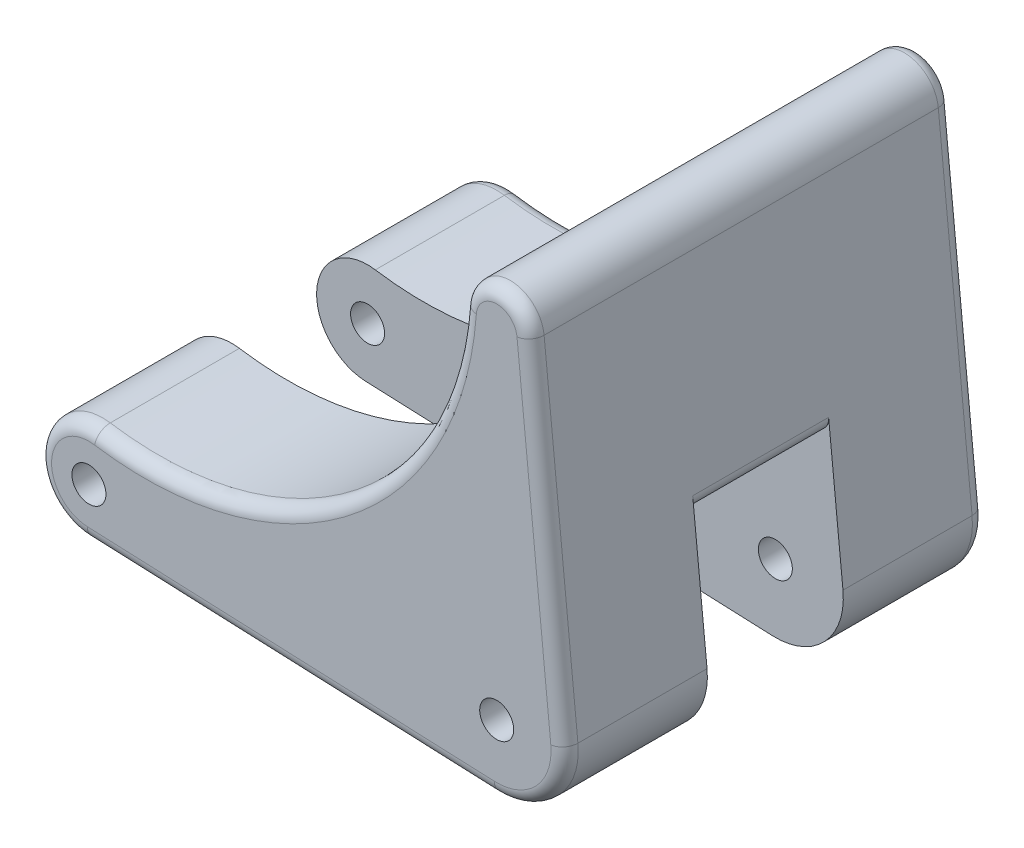
SolidWorks part; units mm, degrees
ref_plane "Front Plane" through (0, 0, 0) normal (0, 0, 1) x (1, 0, 0)
ref_plane "Top Plane" through (0, 0, 0) normal (0, 1, 0) x (1, 0, 0)
ref_plane "Right Plane" through (0, 0, 0) normal (1, 0, 0) x (0, 0, -1)
sketch "Sketch1" plane through (0, 0, 0) normal (0, 0, 1) x (1, 0, 0)
  line L0 (-76.5969, -9.5167) -> (-0.5292, -12.689)
  line L1 (6.3182, 64.135) -> (12.6363, 1.27)
  circle A0 centre (-76.2, 0) radius 3.175
  circle A1 centre (0, 0) radius 3.175
  circle A2 centre (-76.2, 0) radius 9.525 construction
  arc A3 (-0.5292, -12.689) -> (12.6363, 1.27) centre (0, 0) ccw
  arc A4 (-74.754, 9.4146) -> (-76.5969, -9.5167) centre (-76.2, 0) ccw
  arc A5 (6.3182, 64.135) -> (-6.3334, 63.959) centre (0, 63.5) ccw
  arc A6 (-74.754, 9.4146) -> (-6.3334, 63.959) centre (-65.7156, 68.2625) ccw
  dimension "D1" = 76.2
  dimension "D2" = 6.35
  dimension "D3" = 6.35
  dimension "D4" = 19.05
  dimension "D5" = 12.7
  dimension "D6" = 6.35
  dimension "D7" = 63.5
extrude "Boss-Extrude1" add sketch "Sketch1" along normal mid plane 78.74
sketch "Sketch3" plane through (-0.5292, -12.689, 0) normal (-0.0417, -0.9991, 0) x (0.9991, -0.0417, 0)
  line L0 (0, 0) -> (-47.1439, 0) construction
  line L2 (0, 39.37) -> (0, -39.37) construction
  line L3 (-117.9956, -12.7) -> (35.0528, -12.7)
  line L4 (-117.9956, -12.7) -> (-117.9956, 12.7)
  line L5 (-117.9956, 12.7) -> (35.0528, 12.7)
  line L6 (35.0528, -12.7) -> (35.0528, 12.7)
  point P6 (-117.9956, 0)
  point P7 (0, 0)
  dimension "D1" = 25.4
extrude "Cut-Extrude1" cut sketch "Sketch3" against normal blind 38.1
fillet "Fillet1" radius 2.54 2 edges at (-23.3828, 26.3972, 0) (10.2519, 24.9945, 0)
fillet "Fillet2" radius 2.54 12 edges at (-0.0883, 69.8494, -39.37) (9.4773, 32.7025, -39.37) (9.239, -8.7138, -39.37) (-38.563, -11.1028, -39.37) (-85.6802, 0.9228, -39.37) (-0.0883, 69.8494, 39.37) (9.4773, 32.7025, 39.37) (9.239, -8.7138, 39.37) (-38.563, -11.1028, 39.37) (-85.6802, 0.9228, 39.37) (-28.6023, 21.7075, -39.37) (-28.6023, 21.7075, 39.37)
